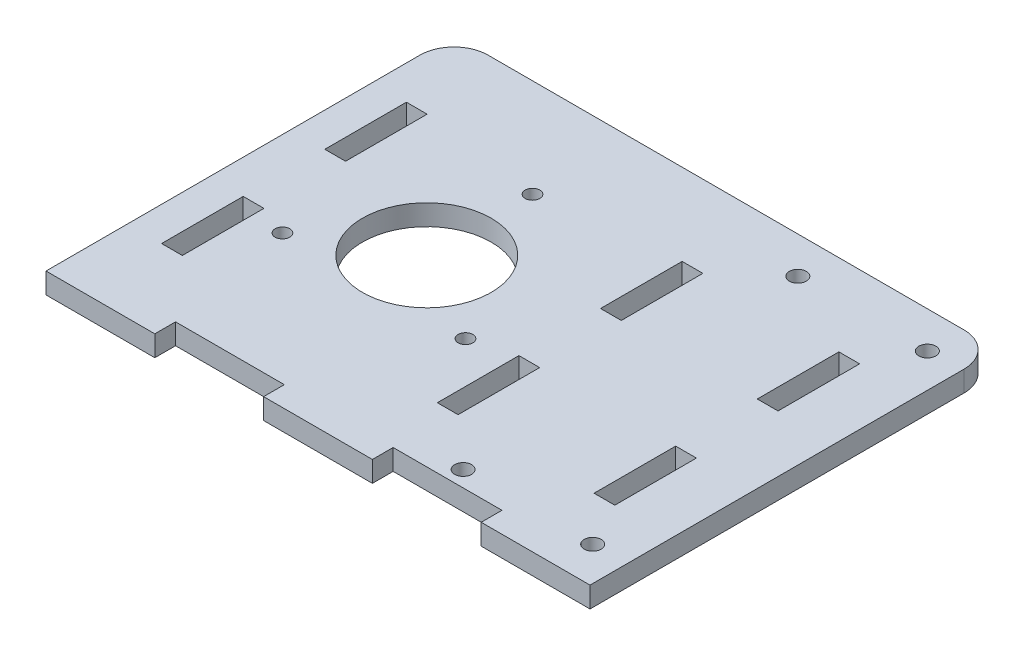
SolidWorks part; units mm, degrees
ref_plane "Front Plane" through (0, 0, 0) normal (0, 0, 1) x (1, 0, 0)
ref_plane "Top Plane" through (0, 0, 0) normal (0, 1, 0) x (1, 0, 0)
ref_plane "Right Plane" through (0, 0, 0) normal (1, 0, 0) x (0, 0, -1)
sketch "Sketch1" plane through (0, 0, 0) normal (0, 1, 0) x (1, 0, 0)
  line L0 (-108, 60) -> (-108, 120) construction
  line L1 (-150, 120) -> (-10, 120)
  line L2 (-160, 110) -> (-160, 0)
  line L3 (-160, 0) -> (-128, 0)
  line L4 (0, 110) -> (0, 0)
  line L5 (-108, 60) -> (-108, 0) construction
  line L6 (-29.05, 109.215) -> (-29.05, 120) construction
  line L7 (-29.05, 10.785) -> (-29.05, 0) construction
  line L8 (-108, 88.93) -> (-108, 78.93) construction
  line L9 (-108, 60) -> (-124.3939, 50.535) construction
  line L10 (-108, 60) -> (-91.6061, 50.535) construction
  line L11 (-81.0761, 44.4555) -> (-82.9459, 45.535) construction
  line L12 (-134.9239, 44.4555) -> (-133.0541, 45.535) construction
  line L13 (-128, 0) -> (-128, 6.1)
  line L14 (-91.6061, 50.535) -> (-82.9459, 45.535) construction
  line L15 (-124.3939, 50.535) -> (-133.0541, 45.535) construction
  line L16 (-48.1, 109.215) -> (-10, 109.215) construction
  line L17 (-48.1, 109.215) -> (-48.1, 10.785) construction
  line L18 (-48.1, 10.785) -> (-10, 10.785) construction
  line L19 (-10, 109.215) -> (-10, 10.785) construction
  line L20 (-128, 6.1) -> (-96, 6.1)
  line L21 (-96, 6.1) -> (-96, 0)
  line L22 (-64, 0) -> (-64, 6.1)
  line L23 (-64, 6.1) -> (-32, 6.1)
  line L24 (-32, 6.1) -> (-32, 0)
  line L25 (-128, 6.1) -> (-160, 6.1) construction
  line L26 (-96, 6.1) -> (-64, 6.1) construction
  line L27 (-32, 6.1) -> (0, 6.1) construction
  line L28 (-143.9, 96) -> (-143.9, 120) construction
  line L29 (-150, 96) -> (-143.9, 96)
  line L30 (-150, 96) -> (-150, 72)
  line L31 (-150, 72) -> (-143.9, 72)
  line L32 (-143.9, 96) -> (-143.9, 72)
  line L33 (-150, 48) -> (-143.9, 48)
  line L34 (-150, 48) -> (-150, 24)
  line L35 (-150, 24) -> (-143.9, 24)
  line L36 (-143.9, 48) -> (-143.9, 24)
  line L37 (-143.9, 72) -> (-143.9, 48) construction
  line L38 (-143.9, 24) -> (-143.9, 0) construction
  line L39 (-62.8, 96) -> (-62.8, 120) construction
  line L40 (-68.9, 96) -> (-62.8, 96)
  line L41 (-68.9, 96) -> (-68.9, 72)
  line L42 (-68.9, 72) -> (-62.8, 72)
  line L43 (-62.8, 96) -> (-62.8, 72)
  line L44 (-68.9, 48) -> (-62.8, 48)
  line L45 (-68.9, 48) -> (-68.9, 24)
  line L46 (-68.9, 24) -> (-62.8, 24)
  line L47 (-62.8, 48) -> (-62.8, 24)
  line L48 (-16.7, 24) -> (-22.8, 24)
  line L49 (-16.7, 24) -> (-16.7, 48)
  line L50 (-16.7, 48) -> (-22.8, 48)
  line L51 (-22.8, 24) -> (-22.8, 48)
  line L52 (-22.8, 96) -> (-16.7, 96)
  line L53 (-22.8, 96) -> (-22.8, 72)
  line L54 (-22.8, 72) -> (-16.7, 72)
  line L55 (-16.7, 96) -> (-16.7, 72)
  line L56 (-62.8, 72) -> (-62.8, 48) construction
  line L57 (-62.8, 24) -> (-62.8, 0) construction
  line L58 (-22.8, 0) -> (-22.8, 24) construction
  line L59 (-22.8, 48) -> (-22.8, 72) construction
  line L60 (-22.8, 96) -> (-22.8, 120) construction
  line L61 (-96, 0) -> (-64, 0)
  line L62 (-32, 0) -> (0, 0)
  circle A0 centre (-108, 60) radius 51 construction
  arc A1 (-150, 120) -> (-160, 110) centre (-150, 110) ccw
  arc A2 (0, 110) -> (-10, 120) centre (-10, 110) ccw
  circle A6 centre (-108, 60) radius 18.93
  circle A7 centre (-108, 91.089) radius 2.159
  circle A8 centre (-81.0761, 44.4555) radius 2.159
  circle A9 centre (-134.9239, 44.4555) radius 2.159
  circle A10 centre (-48.1, 109.215) radius 2.5
  circle A11 centre (-48.1, 10.785) radius 2.5
  circle A12 centre (-10, 10.785) radius 2.5
  circle A13 centre (-10, 109.215) radius 2.5
  point P14 (-160, 120)
  dimension "D3" = 75
  dimension "D12" = 6.1
  dimension "D19" = 37.86
  dimension "D20" = 4.318
  dimension "D24" = 31.089
  dimension "D27" = 5
  dimension "D5" = 52
  dimension "D6" = 102
  dimension "D8" = 10
  dimension "D9" = 10
  dimension "D4" = 120
  dimension "D7" = 10
  dimension "D10" = 6.1
  dimension "D11" = 6.1
  dimension "D13" = 40
  dimension "D14" = 6.1
  dimension "D15" = 10
  dimension "D16" = 96
  dimension "D17" = 160
  dimension "D21" = 10
  dimension "D22" = 120
  dimension "D23" = 120
  dimension "D25" = 38.1
  dimension "D26" = 98.43
extrude "Boss-Extrude1" add sketch "Sketch1" along normal blind 6.096 contours L4 A2 L1 A1 L2 L3 L13 L20 L21 L22 L23 L24 A13 A12 A11 A10 A9 A8 A7 A6 L52 L55 L54 L53 L44 L47 L46 L45 L33 L36 L35 L34 L29 L32 L31 L30
equation "\"mat\"= 6.1"
